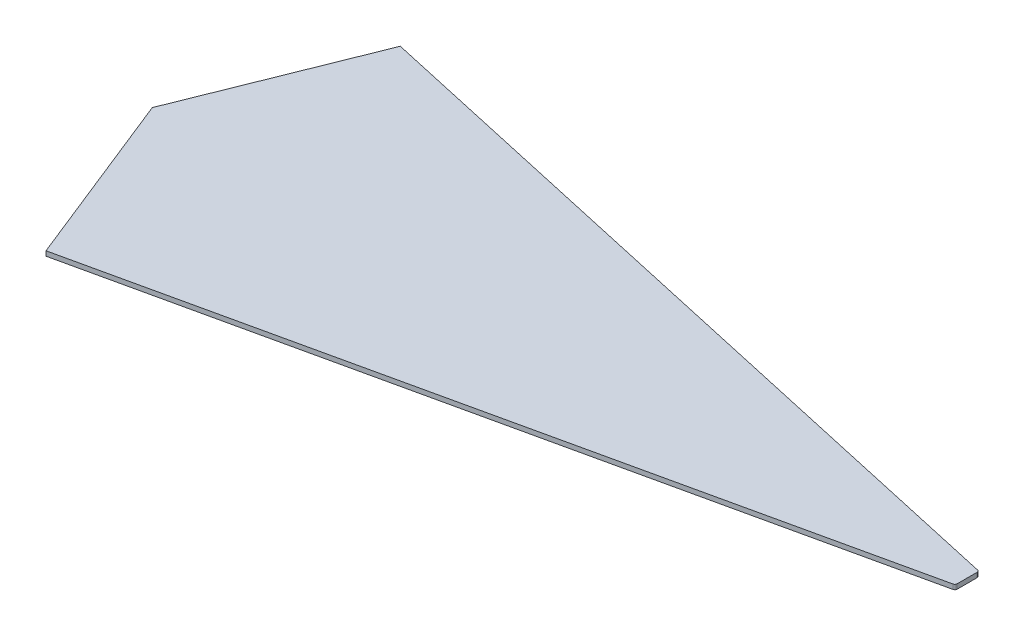
SolidWorks part; units mm, degrees
ref_plane "Front Plane" through (0, 0, 0) normal (0, 0, 1) x (1, 0, 0)
ref_plane "Top Plane" through (0, 0, 0) normal (0, 1, 0) x (1, 0, 0)
ref_plane "Right Plane" through (0, 0, 0) normal (1, 0, 0) x (0, 0, -1)
sketch "Sketch1" plane through (0, 0, 0) normal (0, 1, 0) x (1, 0, 0)
  line L0 (-1000, 0) -> (49000, 0) construction
  line L1 (0, -1000) -> (0, 49000) construction
sketch "Sketch2" plane through (0, 0, 0) normal (0, 1, 0) x (1, 0, 0)
  line L0 (0, 7.5) -> (0, -7.5)
  line L2 (0, -201000) -> (0, 249000) construction
  line L3 (0, 0) -> (-3, 0)
  line L4 (-201000, 0) -> (249000, 0) construction
  line L5 (-3, 0) -> (0, 7.5)
  line L6 (-3, 0) -> (0, -7.5)
  line L7 (0, 0) -> (31.5, 0)
  line L8 (31.5, 0.5) -> (31.5, -0.5)
  line L9 (0, 7.5) -> (31.5, 0.5)
  line L10 (0, -7.5) -> (31.5, -0.5)
  point P5 (0, 0)
  point P14 (31.5, 0)
  dimension "D1" = 15
  dimension "D2" = 3
  dimension "D3" = 31.5
  dimension "D4" = 1
extrude "Boss-Extrude1" add sketch "Sketch2" along normal blind 0.2 contours L10 L8 L9 L5 L6
sketch "Sketch3" plane through (0, 0.2, 0) normal (0, 1, 0) x (1, 0, 0)
  line L0 (0, 7.5) -> (0, -7.5) construction
  line L1 (0, 0) -> (-3, 0) construction
  circle A0 centre (0, 0) radius 2.5
  dimension "D1" = 5
fillet "Fillet4" radius 0.1 1 edges at (31.5, 0.1, 0.5)
fillet "Fillet5" radius 0.1 1 edges at (31.5, 0.1, -0.5)
